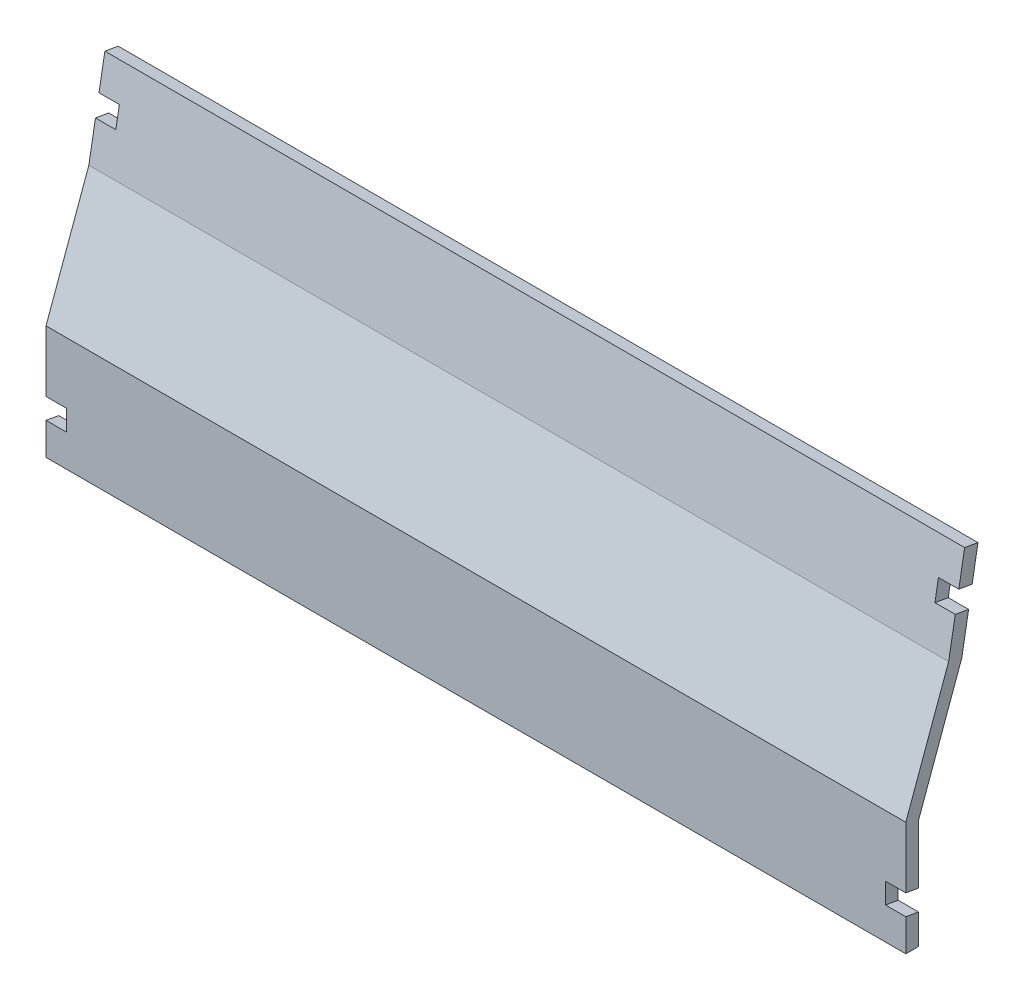
SolidWorks part; units mm, degrees
ref_plane "Front Plane" through (0, 0, 0) normal (0, 0, 1) x (1, 0, 0)
ref_plane "Top Plane" through (0, 0, 0) normal (0, 1, 0) x (1, 0, 0)
ref_plane "Right Plane" through (0, 0, 0) normal (1, 0, 0) x (0, 0, -1)
sketch "Sketch1" plane through (0, 0, 0) normal (1, 0, 0) x (0, 0, -1)
  line L18 (222.8109, 3.8158) -> (227.8137, 2.9336)
  line L19 (227.8137, 2.9336) -> (221.7402, -31.5111)
  line L20 (216.8145, -30.1913) -> (200.7679, -74.2792)
  line L21 (222.8109, 3.8158) -> (216.8145, -30.1913)
  line L22 (216.8145, -30.1913) -> (200.7679, -74.2792)
  line L23 (222.8109, 3.8158) -> (216.8145, -30.1913)
  line L24 (200.7679, -74.2792) -> (205.5415, -76.0167) construction
  line L25 (205.5415, -76.0167) -> (221.7402, -31.5111)
  line L26 (205.5415, -76.0167) -> (205.5415, -116.9647)
  line L27 (205.5415, -116.9647) -> (200.7679, -116.9647)
  line L28 (200.7679, -116.9647) -> (200.7679, -74.2792)
  line L29 (198.381, -142.3647) -> (218.701, -142.3647) construction
  dimension "D1" = 2.54
  dimension "D2" = 5.08
  dimension "D3" = 25.4
extrude "Boss-Extrude1" add sketch "Sketch1" along normal blind 322.072
sketch "Sketch9" plane through (0, 0, 0) normal (-1, 0, 0) x (0, 0, 1)
  line L0 (-228.475, -9.9831) -> (-213.4666, -7.3368) construction
  line L1 (-228.475, -9.9831) -> (-213.4666, -7.3368)
  line L2 (-213.4666, -7.3368) -> (-212.1434, -14.841)
  line L3 (-210.1238, -26.2946) -> (-215.9272, 6.6183) construction
  line L4 (-212.1434, -14.841) -> (-227.1518, -17.4874)
  line L5 (-212.5844, -12.3396) -> (-227.5929, -14.986) construction
  line L6 (-227.1518, -17.4874) -> (-228.475, -9.9831)
  line L7 (-227.5929, -14.986) -> (-228.475, -9.9831) construction
  line L8 (-209.0072, -98.6441) -> (-193.9988, -95.9977) construction
  line L9 (-209.0072, -98.6441) -> (-193.9988, -95.9977)
  line L10 (-193.9988, -95.9977) -> (-193.9988, -103.7353)
  line L11 (-193.9988, -140.4477) -> (-193.9988, -70.5977) construction
  line L12 (-193.9988, -103.7353) -> (-207.684, -106.1484)
  line L13 (-207.684, -106.1484) -> (-209.0072, -98.6441)
  line L14 (-208.1251, -103.647) -> (-209.0072, -98.6441) construction
  line L15 (-193.9988, -101.1561) -> (-208.1251, -103.647) construction
  point P19 (-213.9213, -100.0297)
  dimension "D1" = 2.54
  dimension "D2" = 2.54
extrude "Cut-Extrude7" cut sketch "Sketch9" against normal blind 7.62
sketch "Sketch10" plane through (322.072, 0, 0) normal (1, 0, 0) x (0, 0, -1)
  line L4 (228.475, -9.9831) -> (213.4666, -7.3368)
  line L5 (213.4666, -7.3368) -> (212.1434, -14.841)
  line L6 (212.1434, -14.841) -> (227.1518, -17.4874)
  line L7 (227.1518, -17.4874) -> (228.475, -9.9831)
  line L8 (228.475, -9.9831) -> (213.4666, -7.3368)
  line L9 (213.4666, -7.3368) -> (212.1434, -14.841)
  line L10 (212.1434, -14.841) -> (227.1518, -17.4874)
  line L11 (227.1518, -17.4874) -> (228.475, -9.9831)
  line L12 (193.9988, -103.7353) -> (207.684, -106.1484)
  line L13 (193.9988, -95.9977) -> (193.9988, -103.7353)
  line L14 (209.0072, -98.6441) -> (193.9988, -95.9977)
  line L15 (207.684, -106.1484) -> (209.0072, -98.6441)
  line L16 (193.9988, -103.7353) -> (207.684, -106.1484)
  line L17 (193.9988, -95.9977) -> (193.9988, -103.7353)
  line L18 (209.0072, -98.6441) -> (193.9988, -95.9977)
  line L19 (207.684, -106.1484) -> (209.0072, -98.6441)
  dimension "D1" = 0
  dimension "D2" = 0
extrude "Cut-Extrude8" cut sketch "Sketch10" against normal blind 7.62
